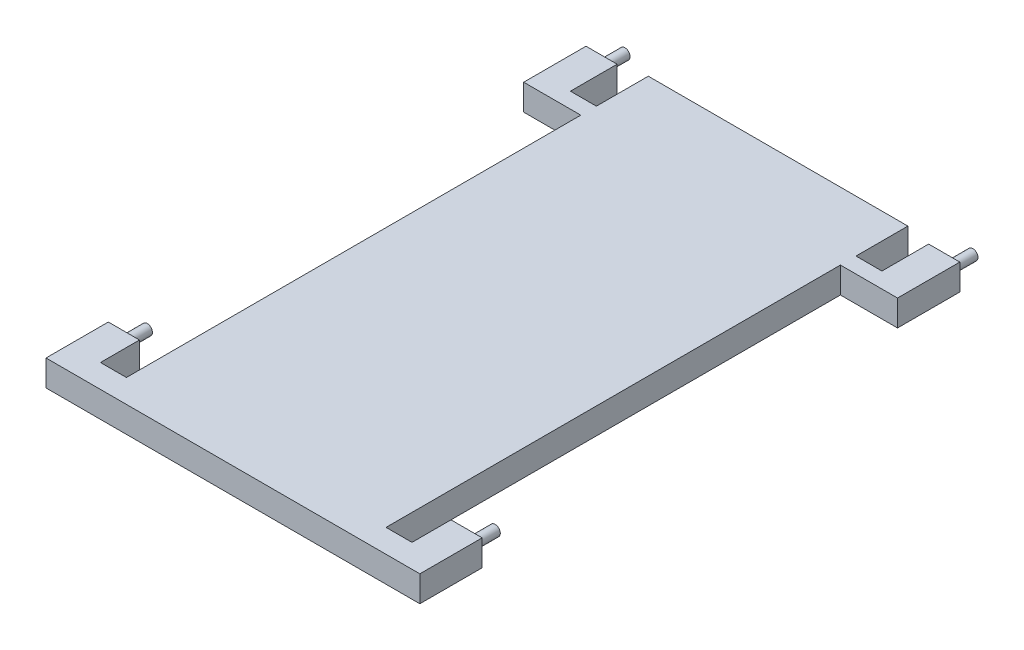
SolidWorks part; units mm, degrees
ref_plane "Front Plane" through (0, 0, 0) normal (0, 0, 1) x (1, 0, 0)
ref_plane "Top Plane" through (0, 0, 0) normal (0, 1, 0) x (1, 0, 0)
ref_plane "Right Plane" through (0, 0, 0) normal (1, 0, 0) x (0, 0, -1)
sketch "Sketch1" plane through (0, 0, 0) normal (0, 1, 0) x (1, 0, 0)
  line L1 (1413.8355, 637.6012) -> (1413.8355, 537.6012)
  line L2 (1413.8355, 537.6012) -> (1463.8355, 537.6012)
  line L3 (1463.8355, 537.6012) -> (1463.8355, 627.6012)
  line L4 (1463.8355, 627.6012) -> (1523.8355, 627.6012)
  line L5 (1523.8355, 627.6012) -> (1523.8355, 507.6012)
  line L6 (1523.8355, 507.6012) -> (1413.8355, 507.6012)
  line L7 (1413.8355, 507.6012) -> (1413.8355, -367.5095)
  line L8 (1413.8355, -367.5095) -> (1463.8355, -367.5095)
  line L9 (1463.8355, -367.5095) -> (1463.8355, -292.3988)
  line L31 (1463.8355, -292.3988) -> (1523.8355, -292.3988)
  line L32 (1523.8355, -292.3988) -> (1523.8355, -412.3988)
  line L33 (1523.8355, -412.3988) -> (1413.8355, -412.3988)
  line L35 (1413.8355, 637.6012) -> (913.8355, 637.6012)
  line L36 (1413.8355, -412.3988) -> (913.8355, -412.3988)
  line L38 (913.8355, 637.6012) -> (913.8355, 537.6012)
  line L39 (913.8355, 537.6012) -> (863.8355, 537.6012)
  line L40 (863.8355, 537.6012) -> (863.8355, 627.6012)
  line L41 (863.8355, 627.6012) -> (803.8355, 627.6012)
  line L42 (803.8355, 627.6012) -> (803.8355, 507.6012)
  line L43 (803.8355, 507.6012) -> (913.8355, 507.6012)
  line L44 (913.8355, 507.6012) -> (913.8355, -367.5095)
  line L45 (913.8355, -367.5095) -> (863.8355, -367.5095)
  line L46 (863.8355, -367.5095) -> (863.8355, -292.3988)
  line L47 (863.8355, -292.3988) -> (803.8355, -292.3988)
  line L48 (803.8355, -292.3988) -> (803.8355, -412.3988)
  line L49 (803.8355, -412.3988) -> (913.8355, -412.3988)
  point P29 (1493.8355, -292.3988)
  dimension "D1" = 60
  dimension "D2" = 100
  dimension "D3" = 120
  dimension "D4" = 50
  dimension "D5" = 110
  dimension "D6" = 800
  dimension "D7" = 50
  dimension "D8" = 30
  dimension "D9" = 60
  dimension "D10" = 120
  dimension "D11" = 110
extrude "Boss-Extrude1" add sketch "Sketch1" along normal blind 50
sketch "Sketch2" plane through (0, 0, -627.6012) normal (0, 0, -1) x (-1, 0, 0)
  line L0 (-863.8355, 50) -> (-803.8355, 50) construction
  line L1 (-803.8355, 50) -> (-803.8355, 0) construction
  circle A0 centre (-828.8355, 25) radius 10
  dimension "D1" = 20
  dimension "D2" = 25
  dimension "D3" = 25
extrude "Boss-Extrude2" add sketch "Sketch2" along normal blind 50
sketch "Sketch3" plane through (0, 0, 292.3988) normal (0, 0, -1) x (-1, 0, 0)
  line L0 (-863.8355, 50) -> (-803.8355, 50) construction
  line L1 (-803.8355, 50) -> (-803.8355, 0) construction
  circle A0 centre (-828.8355, 25) radius 10
  dimension "D1" = 25
  dimension "D2" = 25
  dimension "D3" = 20
extrude "Boss-Extrude3" add sketch "Sketch3" along normal blind 50
sketch "Sketch4" plane through (0, 0, -627.6012) normal (0, 0, -1) x (-1, 0, 0)
  line L0 (-1523.8355, 50) -> (-1523.8355, 0) construction
  line L1 (-1523.8355, 50) -> (-1463.8355, 50) construction
  circle A0 centre (-1498.8355, 25) radius 10
  dimension "D1" = 25
  dimension "D2" = 25
  dimension "D3" = 20
extrude "Boss-Extrude4" add sketch "Sketch4" along normal blind 50
sketch "Sketch5" plane through (0, 0, 292.3988) normal (0, 0, -1) x (-1, 0, 0)
  line L0 (-1523.8355, 50) -> (-1463.8355, 50) construction
  line L2 (-1523.8355, 50) -> (-1523.8355, 0) construction
  circle A0 centre (-1498.8355, 25) radius 10
  dimension "D1" = 20
  dimension "D2" = 25
  dimension "D3" = 25
extrude "Boss-Extrude5" add sketch "Sketch5" along normal blind 50
